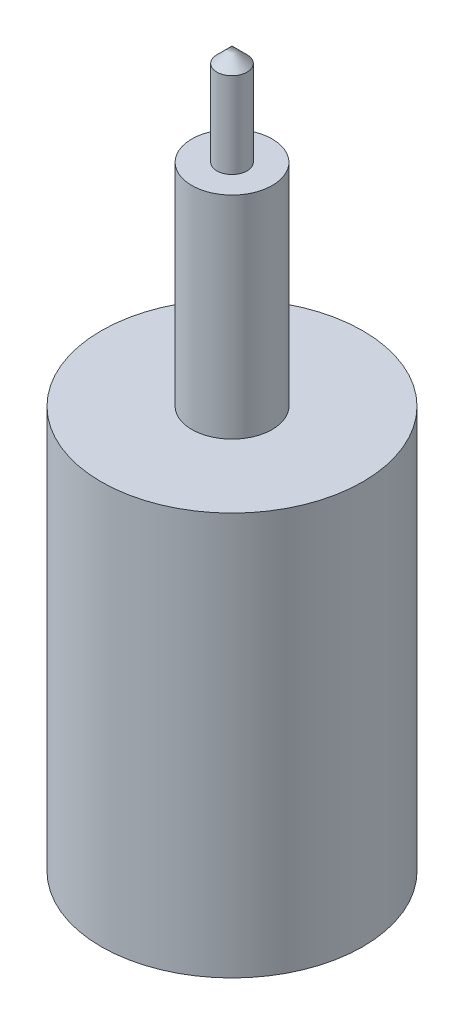
SolidWorks part; units mm, degrees
ref_plane "Front Plane" through (0, 0, 0) normal (0, 0, 1) x (1, 0, 0)
ref_plane "Top Plane" through (0, 0, 0) normal (0, 1, 0) x (1, 0, 0)
ref_plane "Right Plane" through (0, 0, 0) normal (1, 0, 0) x (0, 0, -1)
sketch "Sketch2" plane through (0, 0, 0) normal (0, 1, 0) x (1, 0, 0)
  circle A0 centre (0, 0) radius 26
  dimension "D1" = 52
extrude "Boss-Extrude1" add sketch "Sketch2" along normal blind 80
sketch "Sketch3" plane through (0, 80, 0) normal (0, 1, 0) x (1, 0, 0)
  circle A0 centre (0, 0) radius 8
  dimension "D1" = 16
extrude "Boss-Extrude2" add sketch "Sketch3" along normal blind 42
sketch "Sketch4" plane through (0, 122, 0) normal (0, 1, 0) x (1, 0, 0)
  circle A0 centre (0, 0) radius 3
  dimension "D1" = 6
extrude "Boss-Extrude3" add sketch "Sketch4" along normal blind 20
chamfer "Chamfer1" distance 3 angle 45 1 edges at (0, 142, 3)
